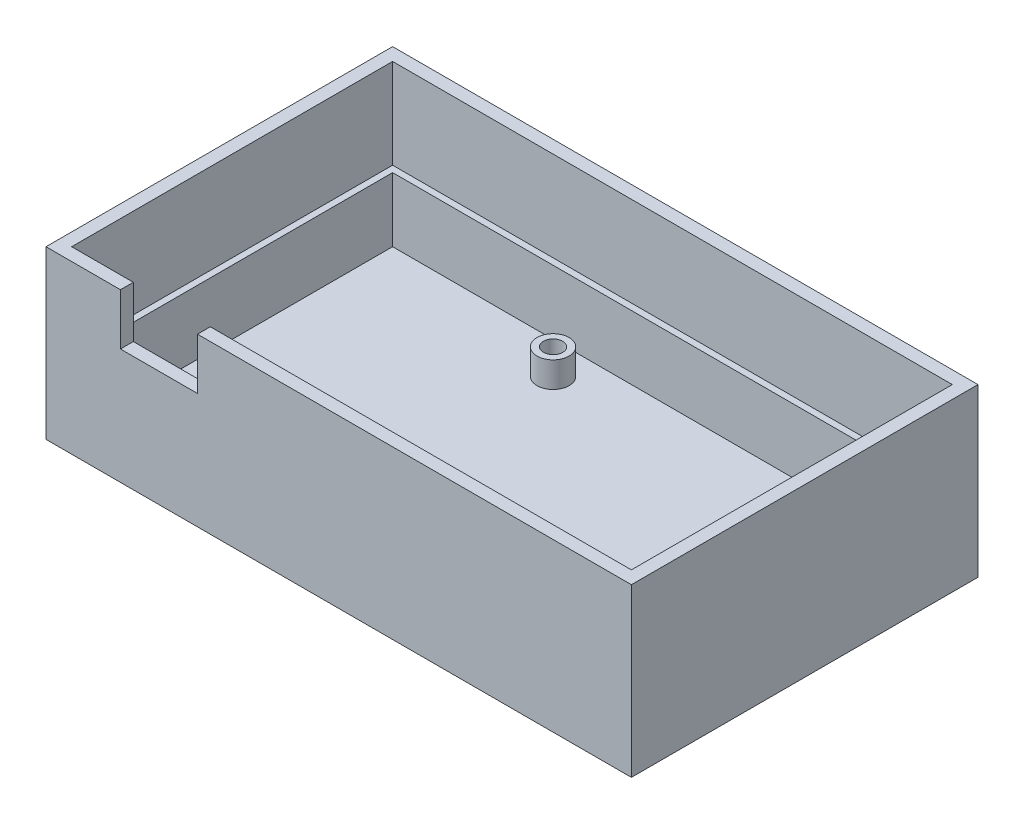
SolidWorks part; units mm, degrees
ref_plane "Alzado" through (0, 0, 0) normal (0, 0, 1) x (1, 0, 0)
ref_plane "Planta" through (0, 0, 0) normal (0, 1, 0) x (1, 0, 0)
ref_plane "Vista lateral" through (0, 0, 0) normal (1, 0, 0) x (0, 0, -1)
sketch "Croquis1" plane through (0, 0, 0) normal (0, 1, 0) x (1, 0, 0)
  line L1 (-36.6, -23) -> (36.6, -23) construction
  line L2 (-36.6, -23) -> (-36.6, 23) construction
  line L3 (-36.6, 23) -> (36.6, 23) construction
  line L4 (36.6, -23) -> (36.6, 23) construction
  line L5 (-36.6, -23) -> (36.6, 23) construction
  line L6 (-36.6, 23) -> (36.6, -23) construction
  line L7 (-42.6, -27) -> (48.6, -27)
  line L8 (-42.6, -27) -> (-42.6, 27)
  line L9 (-42.6, 27) -> (48.6, 27)
  line L10 (48.6, -27) -> (48.6, 27)
  point P0 (0, 0)
  point P6 (0, 0)
  dimension "D1" = 46
  dimension "D2" = 73.2
  dimension "D3" = 4
  dimension "D4" = 12
  dimension "D5" = 6
  dimension "D6" = 4
  dimension "D7" = 91.2
  dimension "D8" = 54
extrude "Saliente-Extruir1" add sketch "Croquis1" along normal blind 2
sketch "Croquis2" plane through (0, 2, 0) normal (0, 1, 0) x (1, 0, 0)
  line L0 (0, 0) -> (-36.6, 0) construction
  line L1 (-36.6, -23) -> (36.6, -23) construction
  line L2 (-36.6, -23) -> (-36.6, 23) construction
  line L3 (-36.6, 23) -> (36.6, 23) construction
  line L4 (36.6, -23) -> (36.6, 23) construction
  line L5 (-36.6, -23) -> (36.6, 23) construction
  line L6 (-36.6, 23) -> (36.6, -23) construction
  line L7 (-9.6, -19) -> (36.6, -19) construction
  line L8 (-9.6, 19) -> (36.6, 19) construction
  circle A0 centre (-9.6, -19) radius 2.5
  circle A1 centre (-9.6, 19) radius 2.5
  circle A2 centre (33.4, 19) radius 2.5
  circle A3 centre (33.4, -19) radius 2.5
  point P0 (0, 0)
  dimension "D4" = 4
  dimension "D5" = 5
  dimension "D6" = 5
  dimension "D7" = 5
  dimension "D8" = 70
  dimension "D9" = 70
  dimension "D1" = 46
  dimension "D2" = 73.2
  dimension "D3" = 27
extrude "Saliente-Extruir2" add sketch "Croquis2" along normal blind 4
sketch "Croquis3" plane through (0, 6, 0) normal (0, 1, 0) x (1, 0, 0)
  circle A0 centre (-9.6, -19) radius 1.5
  circle A1 centre (33.4, -19) radius 1.5
  circle A2 centre (33.4, 19) radius 1.5
  circle A3 centre (-9.6, 19) radius 1.5
  dimension "D1" = 3
  dimension "D2" = 3
  dimension "D3" = 3
  dimension "D4" = 3
extrude "Cortar-Extruir1" cut sketch "Croquis3" against normal blind 4
sketch "Croquis4" plane through (0, 2, 0) normal (0, 1, 0) x (1, 0, 0)
  line L1 (-36.7, -23) -> (36.7, -23) construction
  line L2 (-36.7, -23) -> (-36.7, 23) construction
  line L3 (-36.7, 23) -> (36.7, 23) construction
  line L4 (36.7, -23) -> (36.7, 23) construction
  line L5 (-36.7, -23) -> (36.7, 23) construction
  line L6 (-36.7, 23) -> (36.7, -23) construction
  line L7 (-42.6, 27) -> (48.6, 27)
  line L8 (-42.6, 27) -> (-42.6, -27)
  line L9 (-42.6, -27) -> (48.6, -27)
  line L10 (48.6, 27) -> (48.6, -27)
  line L11 (-39.6, 24) -> (45.6, 24)
  line L12 (-39.6, 24) -> (-39.6, -24)
  line L13 (-39.6, -24) -> (45.6, -24)
  line L14 (45.6, 24) -> (45.6, -24)
  point P0 (0, 0)
  dimension "D3" = 3
  dimension "D4" = 3
  dimension "D1" = 46
  dimension "D2" = 73.4
  dimension "D5" = 3
  dimension "D6" = 3
extrude "Saliente-Extruir3" add sketch "Croquis4" along normal blind 24
sketch "Croquis7" plane through (0, 26, 0) normal (0, 1, 0) x (1, 0, 0)
  line L5 (-39.6, 24) -> (-39.6, -24) construction
  line L6 (-40.6, -25) -> (46.6, -25)
  line L8 (-40.6, -25) -> (-40.6, 25)
  line L9 (-40.6, 25) -> (46.6, 25)
  line L10 (46.6, -25) -> (46.6, 25)
  line L11 (45.6, -24) -> (45.6, 24) construction
  line L12 (-39.6, -24) -> (45.6, -24) construction
  line L13 (45.6, 24) -> (-39.6, 24) construction
  dimension "D1" = 1
  dimension "D2" = 1
  dimension "D3" = 1
  dimension "D4" = 1
extrude "Cortar-Extruir2" cut sketch "Croquis7" against normal blind 14
sketch "Croquis9" plane through (0, 26, 0) normal (0, 1, 0) x (1, 0, 0)
  line L0 (-42.6, 27) -> (-42.6, -27) construction
  line L1 (36.5, -23) -> (-36.5, -23) construction
  line L2 (36.5, -23) -> (36.5, 23) construction
  line L3 (36.5, 23) -> (-36.5, 23) construction
  line L4 (-36.5, -23) -> (-36.5, 23) construction
  line L5 (36.5, -23) -> (-36.5, 23) construction
  line L6 (36.5, 23) -> (-36.5, -23) construction
  line L7 (-19, -35.5) -> (-31, -35.5)
  line L8 (-19, -35.5) -> (-19, -10.5)
  line L9 (-19, -10.5) -> (-31, -10.5)
  line L10 (-31, -35.5) -> (-31, -10.5)
  line L11 (-19, -35.5) -> (-31, -10.5) construction
  line L12 (-19, -10.5) -> (-31, -35.5) construction
  point P0 (0, 0)
  point P6 (-25, -23)
  point P11 (-25, -10.5)
  dimension "D1" = 46
  dimension "D2" = 73
  dimension "D3" = 11.5
  dimension "D4" = 25
  dimension "D5" = 12
  dimension "D6" = 6.1
extrude "Cortar-Extruir3" cut sketch "Croquis9" against normal blind 8
equation "\"D2@Croquis3\"=\"D1@Croquis3\""
equation "\"D3@Croquis3\"=\"D1@Croquis3\""
equation "\"D4@Croquis3\"=\"D1@Croquis3\""
equation "\"D6@Croquis4\"=\"D5@Croquis4\""
